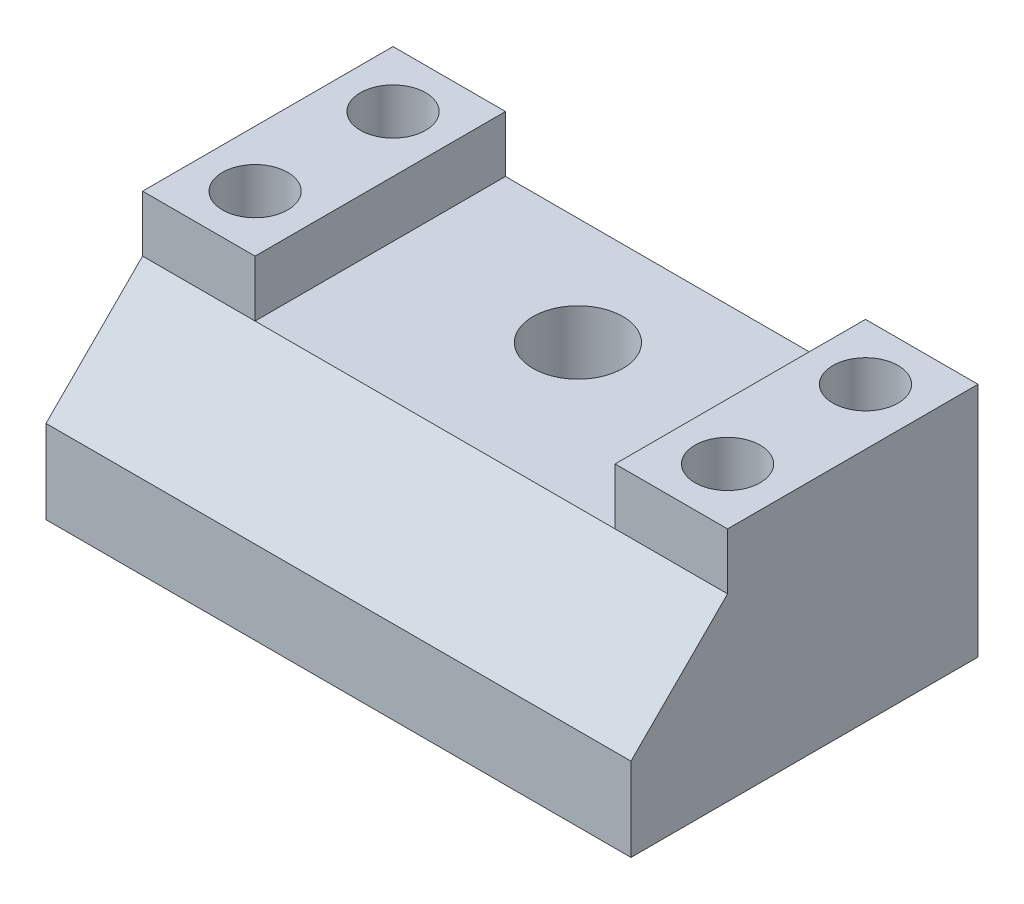
SolidWorks part; units mm, degrees
ref_plane "Front Plane" through (0, 0, 0) normal (0, 0, 1) x (1, 0, 0)
ref_plane "Top Plane" through (0, 0, 0) normal (0, 1, 0) x (1, 0, 0)
ref_plane "Right Plane" through (0, 0, 0) normal (1, 0, 0) x (0, 0, -1)
sketch "Sketch1" plane through (0, 0, 0) normal (0, 1, 0) x (1, 0, 0)
  line L0 (0, 0) -> (0, -13.7) construction
  line L1 (-16, 9.5616) -> (16, 9.5616)
  line L2 (16, 9.5616) -> (16, -13.7)
  line L3 (16, -13.7) -> (-16, -13.7)
  line L4 (-16, -13.7) -> (-16, 9.5616)
  line L5 (0, 9.5616) -> (0, 0) construction
  circle A0 centre (0, 0) radius 4
  dimension "D1" = 8
  dimension "D2" = 13.7
  dimension "D3" = 32
extrude "Boss-Extrude1" add sketch "Sketch1" against normal blind 10
sketch "Sketch3" plane through (0, -10, 0) normal (0, -1, 0) x (1, 0, 0)
  line L0 (-16, 13.7) -> (16, 13.7) construction
  line L1 (-16, 13.7) -> (-26, 13.7)
  line L2 (-16, 13.7) -> (-16, -9.5616)
  line L3 (-16, -9.5616) -> (-26, -9.5616)
  line L4 (-26, 13.7) -> (-26, -9.5616)
  line L5 (16, -9.5616) -> (26, -9.5616)
  line L6 (16, -9.5616) -> (16, 13.7)
  line L7 (16, 13.7) -> (26, 13.7)
  line L8 (26, -9.5616) -> (26, 13.7)
  line L9 (16, -9.5616) -> (-16, -9.5616) construction
  dimension "D1" = 10
extrude "Boss-Extrude2" add sketch "Sketch3" against normal blind 15
sketch "Sketch5" plane through (0, 0, 13.7) normal (0, 0, 1) x (1, 0, 0)
  line L8 (16, 0) -> (-16, 0)
  line L9 (-16, 0) -> (-16, 5)
  line L10 (-16, 5) -> (-26, 5)
  line L11 (-26, 5) -> (-26, -10)
  line L12 (-26, -10) -> (26, -10)
  line L13 (26, -10) -> (26, 5)
  line L14 (26, 5) -> (16, 5)
  line L15 (16, 5) -> (16, 0)
  line L16 (16, 0) -> (-16, 0)
  line L17 (-16, 0) -> (-16, 5)
  line L18 (-16, 5) -> (-26, 5)
  line L19 (-26, 5) -> (-26, -10)
  line L20 (-26, -10) -> (26, -10)
  line L21 (26, -10) -> (26, 5)
  line L22 (26, 5) -> (16, 5)
  line L23 (16, 5) -> (16, 0)
  dimension "D1" = 0
extrude "Boss-Extrude3" add sketch "Sketch5" along normal blind 15
sketch "Sketch6" plane through (-26, 0, 0) normal (-1, 0, 0) x (0, 0, 1)
  line L4 (28.7, 0) -> (-9.5616, 0) construction
  line L5 (28.7, 0) -> (-9.5616, 0) construction
  line L6 (12.7, 0) -> (22.7, -10)
  line L7 (28.7, -10) -> (-9.5616, -10) construction
  line L8 (22.7, -10) -> (28.7, -10)
  line L9 (28.7, -10) -> (28.7, 5)
  line L10 (28.7, 5) -> (12.7, 5)
  line L11 (28.7, 5) -> (-9.5616, 5) construction
  line L12 (12.7, 5) -> (12.7, 0)
  dimension "D1" = 16
  dimension "D2" = 45
extrude "Cut-Extrude1" cut sketch "Sketch6" against normal through all
sketch "Sketch7" plane through (0, 5, 0) normal (0, 1, 0) x (1, 0, 0)
  line L0 (21, 4.5616) -> (21, 9.5616) construction
  line L1 (16, 9.5616) -> (26, 9.5616) construction
  line L3 (-21, 9.5616) -> (-21, 4.5616) construction
  line L4 (-26, 9.5616) -> (-16, 9.5616) construction
  line L6 (26, -12.7) -> (16, -12.7) construction
  point P0 (21, 4.5616)
  point P4 (-21, 4.5616)
  point P5 (-21, -7.7)
  point P6 (21, -7.7)
  dimension "D3" = 5
  dimension "D4" = 5
  dimension "D1" = 2
  dimension "D2" = 2
hole_wizard "M5 Clearance Hole1" positions "Sketch7" profile "Sketch8" hole size "M5" standard "ISO" end condition through all
sketch "Sketch8" plane through (21, 5, -4.5616) normal (1, 0, 0) x (0, 0, 1)
  line L0 (0, 0) -> (0, 15)
  line L1 (0, 15) -> (2.9, 15)
  line L2 (2.9, 15) -> (2.9, 0)
  line L5 (2.9, 0) -> (0, 0)
  line L11 (0, -6.35) -> (0, 107.95) construction
  dimension "Thru Hole Dia." = 5.8
  dimension "Thru Hole Depth" = 15
chamfer "Chamfer1" distance 2 angle 45 1 edges at (0, -10, 22.7)
sketch "Sketch9" plane through (0, -10, 0) normal (0, -1, 0) x (1, 0, 0)
  line L4 (26, -9.5616) -> (26, 21.2858)
  line L5 (26, 21.2858) -> (-26, 21.2858)
  line L6 (-26, 21.2858) -> (-26, -9.5616)
  line L7 (-26, -9.5616) -> (26, -9.5616)
  line L8 (26, -9.5616) -> (26, 21.2858)
  line L9 (26, 21.2858) -> (-26, 21.2858)
  line L10 (-26, 21.2858) -> (-26, -9.5616)
  line L11 (-26, -9.5616) -> (26, -9.5616)
  circle A0 centre (21, -4.5616) radius 2.9 construction
  circle A1 centre (21, 7.7) radius 2.9 construction
  circle A2 centre (0, 0) radius 4 construction
  circle A3 centre (-21, -4.5616) radius 2.9 construction
  circle A4 centre (-21, 7.7) radius 2.9 construction
  circle A5 centre (21, -4.5616) radius 2.9
  circle A6 centre (21, 7.7) radius 2.9
  circle A7 centre (0, 0) radius 4
  circle A8 centre (-21, -4.5616) radius 2.9
  circle A9 centre (-21, 7.7) radius 2.9
  dimension "D1" = 0
extrude "Boss-Extrude4" add sketch "Sketch9" along normal blind 6
